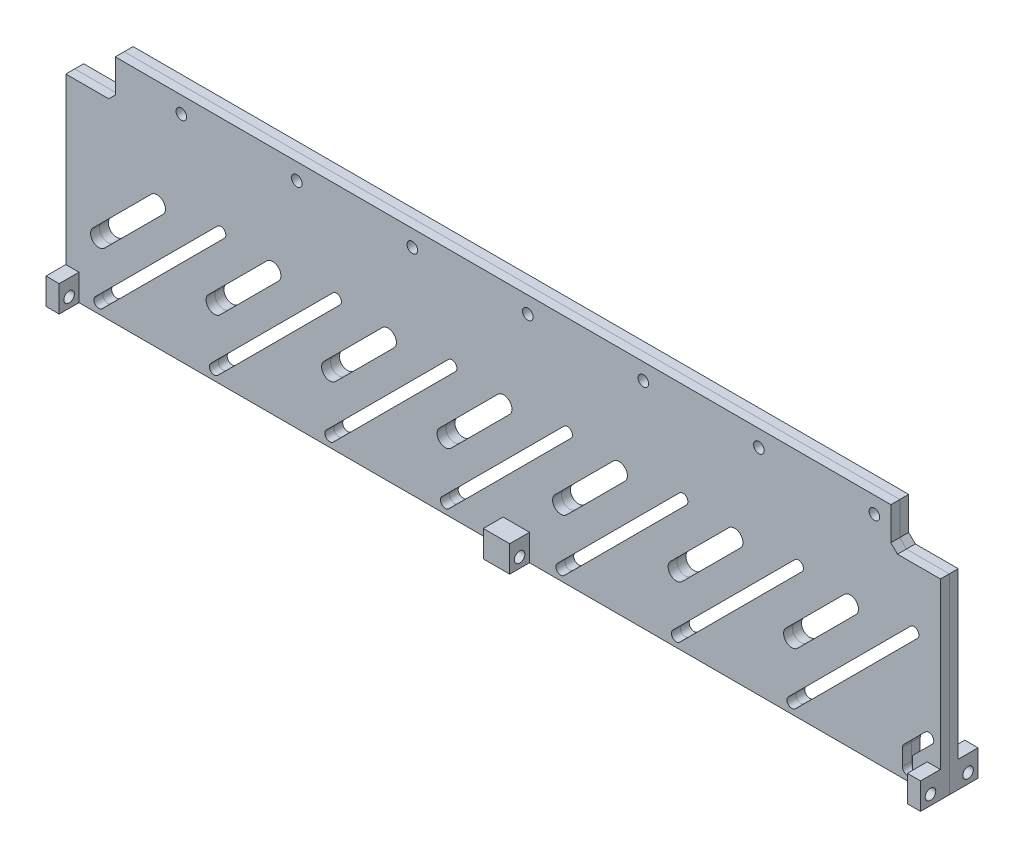
SolidWorks part; units mm, degrees
ref_plane "前视基准面" through (0, 0, 0) normal (0, 0, 1) x (1, 0, 0)
ref_plane "上视基准面" through (0, 0, 0) normal (0, 1, 0) x (1, 0, 0)
ref_plane "右视基准面" through (0, 0, 0) normal (1, 0, 0) x (0, 0, -1)
sketch "草图1" plane through (0, 0, 0) normal (0, 0, 1) x (1, 0, 0)
  line L1 (-132.5, 35) -> (132.5, 35)
  line L2 (-132.5, 35) -> (-132.5, -35)
  line L3 (-132.5, -35) -> (132.5, -35)
  line L4 (132.5, 35) -> (132.5, -35)
  line L5 (-132.5, 35) -> (132.5, -35) construction
  line L6 (-132.5, -35) -> (132.5, 35) construction
  point P0 (0, 0)
  dimension "D1" = 265
  dimension "D2" = 70
extrude "凸台-拉伸1" add sketch "草图1" along normal blind 2.7
sketch "草图11" plane through (0, 0, 2.7) normal (0, 0, 1) x (1, 0, 0)
  line L0 (-132.5, 35) -> (-132.5, 23)
  line L1 (-132.5, 35) -> (-132.5, -35) construction
  line L2 (-132.5, 23) -> (-119.5, 23)
  line L3 (-119.5, 23) -> (-117.5, 25)
  line L4 (-117.5, 25) -> (-117.5, 35)
  line L5 (132.5, 35) -> (-132.5, 35) construction
  line L6 (-117.5, 35) -> (-132.5, 35)
  line L13 (0, 35) -> (0, -35) construction
  line L14 (-132.5, -35) -> (132.5, -35) construction
  line L15 (117.5, 35) -> (132.5, 35)
  line L16 (117.5, 25) -> (117.5, 35)
  line L17 (119.5, 23) -> (117.5, 25)
  line L18 (132.5, 23) -> (119.5, 23)
  line L19 (132.5, 35) -> (132.5, 23)
  dimension "D1" = 15
  dimension "D2" = 12
  dimension "D3" = 135
  dimension "D4" = 10
extrude "切除-拉伸5" cut sketch "草图11" against normal blind 10
sketch "草图2" plane through (0, 0, 2.7) normal (0, 0, 1) x (1, 0, 0)
  line L1 (0, -32) -> (0, 35) construction
  line L2 (117.5, 35) -> (-117.5, 35) construction
  line L3 (-132.5, 23) -> (-132.5, -35) construction
  line L4 (-122.5, -32) -> (-85.5, 5) construction
  line L5 (-123.5607, -30.9393) -> (-86.5607, 6.0607)
  line L6 (-121.4393, -33.0607) -> (-84.4393, 3.9393)
  line L7 (-132.5, -35) -> (132.5, -35) construction
  line L8 (-103.0546, 0.8805) -> (-120.7322, -16.7972)
  line L9 (-124.2678, -13.2617) -> (-106.5901, 4.416)
  line L11 (-132.5, 23) -> (-132.5, -35) construction
  arc A1 (-123.5607, -30.9393) -> (-121.4393, -33.0607) centre (-122.5, -32) ccw
  arc A2 (-84.4393, 3.9393) -> (-86.5607, 6.0607) centre (-85.5, 5) ccw
  circle A6 centre (-97.5, 30) radius 1.6
  arc A8 (-120.7322, -16.7972) -> (-124.2678, -13.2617) centre (-122.5, -15.0294) cw
  arc A11 (-106.5901, 4.416) -> (-103.0546, 0.8805) centre (-104.8223, 2.6482) cw
  point P4 (-104, -13.5)
  dimension "D6" = 35
  dimension "D11" = 5
  dimension "D7" = 3.2
  dimension "D2" = 3
  dimension "D3" = 45
  dimension "D4" = 3
  dimension "D5" = 40
  dimension "D8" = 65
  dimension "D10" = 10
  dimension "D13" = 8
  dimension "D16" = 25
extrude "切除-拉伸1" cut sketch "草图2" against normal through all
pattern_linear "阵列(线性)1" count 7 spacing 35 along (1, 0, 0) of "切除-拉伸1"
sketch "草图10" plane through (0, 0, 2.7) normal (0, 0, 1) x (1, 0, 0)
  line L0 (122.5, -32) -> (122.5, -27) construction
  line L1 (121, -32) -> (121, -27)
  line L2 (124, -32) -> (124, -27.6213)
  line L3 (122.5, -27) -> (129, -20.5) construction
  line L4 (121.4393, -25.9393) -> (127.9393, -19.4393)
  line L5 (124, -27.6213) -> (130.0607, -21.5607)
  line L6 (87.5, -32) -> (122.5, -32) construction
  line L7 (132.5, -35) -> (132.5, 23) construction
  line L8 (88.5607, -33.0607) -> (125.5607, 3.9393) construction
  line L9 (130.5, -8.3623) -> (130.5, -26.4353) construction
  arc A0 (121, -32) -> (124, -32) centre (122.5, -32) ccw
  arc A2 (121.4393, -25.9393) -> (121, -27) centre (122.5, -27) ccw
  arc A3 (130.0607, -21.5607) -> (127.9393, -19.4393) centre (129, -20.5) ccw
  point P2 (122.5, -29.5)
  point P7 (125.75, -23.75)
  dimension "D1" = 3
  dimension "D2" = 3
  dimension "D3" = 10
  dimension "D4" = 2
  dimension "D5" = 5
extrude "切除-拉伸4" cut sketch "草图10" against normal through all
sketch "草图5" plane through (0, 0, 2.7) normal (0, 0, 1) x (1, 0, 0)
  line L0 (-132.5, -35) -> (132.5, -35) construction
  line L1 (-132.5, -35) -> (-128.5, -35)
  line L2 (-132.5, -35) -> (-132.5, -27)
  line L3 (-132.5, -27) -> (-128.5, -27)
  line L4 (-128.5, -35) -> (-128.5, -27)
  line L5 (132.5, -35) -> (128.5, -35)
  line L6 (132.5, -35) -> (132.5, -27)
  line L7 (132.5, -27) -> (128.5, -27)
  line L8 (128.5, -35) -> (128.5, -27)
  line L9 (0, -35) -> (8, -35)
  line L10 (0, -35) -> (0, -27)
  line L11 (0, -27) -> (8, -27)
  line L12 (8, -35) -> (8, -27)
  line L13 (17.5, -32) -> (4, -32) construction
  line L14 (4, -32) -> (4, -27) construction
  dimension "D1" = 8
  dimension "D2" = 8
  dimension "4" = 4
  dimension "D3" = 13.5
extrude "凸台-拉伸3" add sketch "草图5" along normal blind 6
sketch "草图7" plane through (-128.5, 0, 0) normal (1, 0, 0) x (0, 0, -1)
  line L0 (-8.7, -35) -> (-2.7, -35) construction
  line L1 (-5.7, -32) -> (-5.7, -35) construction
  circle A0 centre (-5.7, -32) radius 1.6
  dimension "D2" = 3.2
  dimension "D1" = 3
extrude "切除-拉伸3" cut sketch "草图7" against normal through all both and the other way through all
mirror "镜向1" about plane through (0, 0, 0) normal (0, 0, 1) of bodies 114
